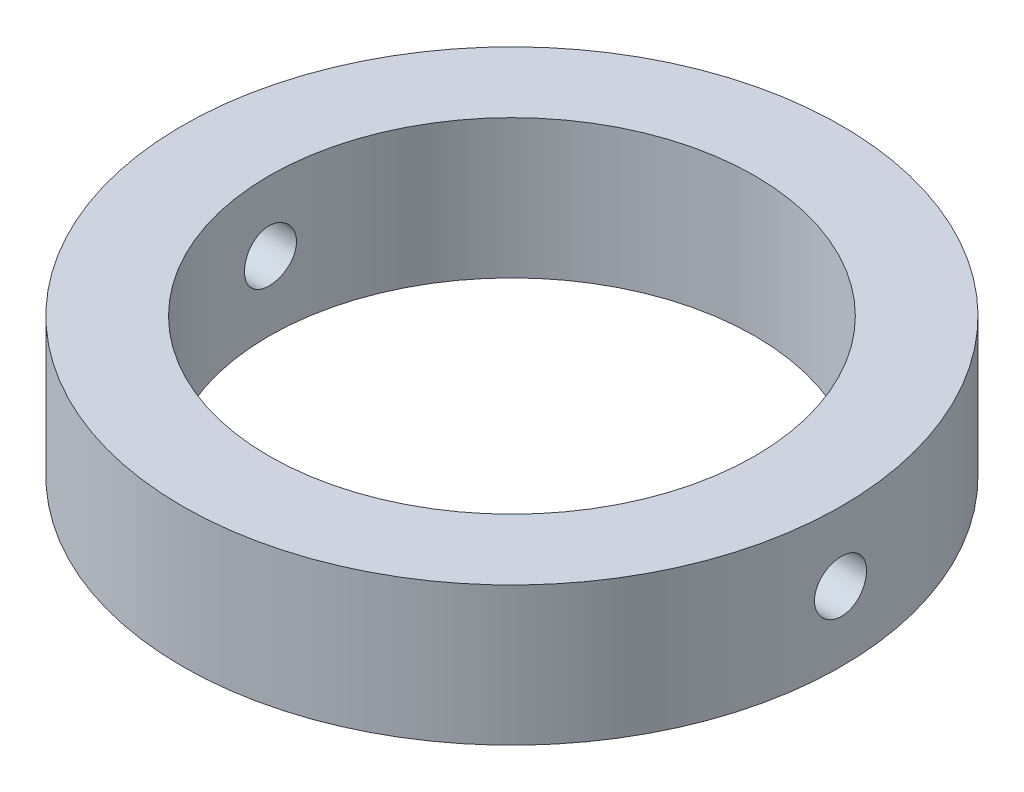
SolidWorks part; units mm, degrees
ref_plane "Спереди" through (0, 0, 0) normal (0, 0, 1) x (1, 0, 0)
ref_plane "Сверху" through (0, 0, 0) normal (0, 1, 0) x (1, 0, 0)
ref_plane "Справа" through (0, 0, 0) normal (1, 0, 0) x (0, 0, -1)
sketch "Эскиз1" plane through (0, 0, 0) normal (0, 1, 0) x (1, 0, 0)
  circle A0 centre (0, 0) radius 28
  circle A1 centre (0, 0) radius 38
  dimension "D1" = 56
  dimension "D2" = 76
extrude "Вытянуть1" add sketch "Эскиз1" along normal blind 16
sketch "Эскиз2" plane through (-48, 0, 0) normal (-1, 0, 0) x (0, 0, 1)
  circle A0 centre (0, 8) radius 3
extrude "Вырез-Вытянуть1" cut sketch "Эскиз2" against normal mid plane 262
